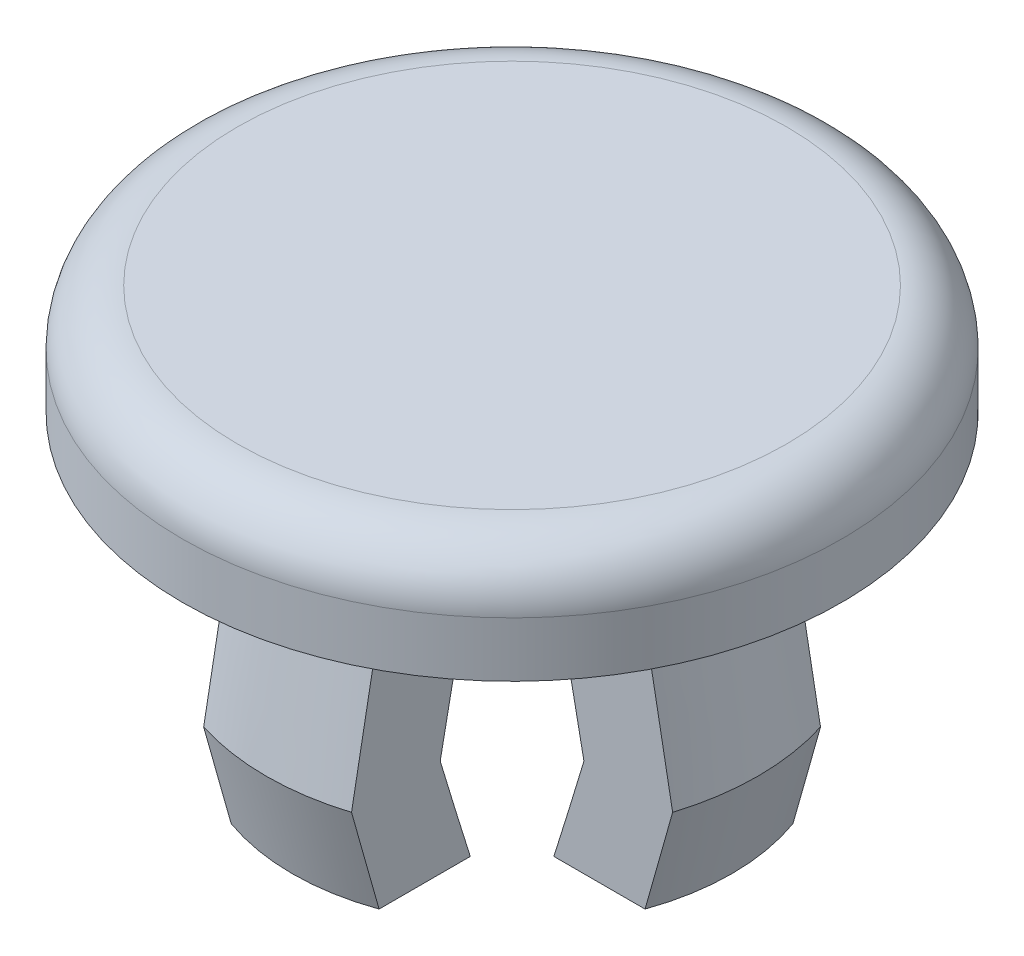
SolidWorks part; units mm, degrees
material "VeroWhite Plus"
ref_plane "Front Plane" through (0, 0, 0) normal (0, 0, 1) x (1, 0, 0)
ref_plane "Top Plane" through (0, 0, 0) normal (0, 1, 0) x (1, 0, 0)
ref_plane "Right Plane" through (0, 0, 0) normal (1, 0, 0) x (0, 0, -1)
sketch "Sketch0" plane through (0, 0, 0) normal (0, 0, 1) x (1, 0, 0)
  line L1 (0, -3.5) -> (0, 2) construction
  line L2 (-6, 2) -> (6, 2) construction
  line L3 (-4, -3.5) -> (4, -3.5) construction
  point P7 (0, -0.8)
  dimension "D" = 12
  dimension "B MAX" = 3.5
  dimension "A" = 8
  dimension "H" = 2
  dimension "B MIN" = 0.8
sketch "Sketch1" plane through (0, 0, 0) normal (0, 0, 1) x (1, 0, 0)
  line L0 (0, 2) -> (-5, 2)
  line L1 (-6, 1) -> (-6, 0)
  line L2 (-6, 1) -> (0, 1) construction
  line L4 (0, 2) -> (0, 0)
  line L5 (0, -3.5) -> (0, 2) construction
  line L7 (0, 0) -> (-6, 0)
  arc A0 (-5, 2) -> (-6, 1) centre (-5, 1) ccw
revolve "Revolve1" add sketch "Sketch1" angle 360 about L4
sketch "Sketch2" plane through (0, 0, 0) normal (0, 0, 1) x (1, 0, 0)
  line L1 (-4, -3.5) -> (-4, -5.2768) construction
  line L2 (-2.9761, -3.5) -> (-4.4761, -3.5) construction
  line L3 (0, 0) -> (-6, 0) construction
  line L4 (-4.4761, -3.5) -> (-4.4761, -1.75) construction
  line L5 (-4.4761, -3.5) -> (-3.8589, 0)
  line L6 (-2.3589, 0) -> (-2.9761, -3.5)
  line L7 (-2.9761, -3.5) -> (-2.5, -5.2768)
  line L8 (-4, -5.2768) -> (-4.4761, -3.5)
  line L9 (-2.5, -5.2768) -> (-4, -5.2768)
  line L10 (-3.8589, 0) -> (-2.3589, 0)
  line L11 (0, -3.5) -> (0, 2) construction
  line L12 (0, -3.5) -> (0, 2) construction
  line L13 (-4, -3.5) -> (-4, -0.8) construction
  line L14 (-4, -0.8) -> (0, -0.8) construction
  line L15 (-4.4761, -1.75) -> (-4.4761, 0) construction
  dimension "D1" = 1.5
  dimension "D2" = 15
  dimension "D3" = 25
revolve "Revolve2" add sketch "Sketch2" angle 360 mid plane about L12
sketch "Sketch3" plane through (0, 0, 0) normal (0, 1, 0) x (1, 0, 0)
  line L0 (-4.2689, 1.346) -> (-1.346, 1.346)
  line L1 (0, 0) -> (-4.2689, -1.346) construction
  line L2 (0, 0) -> (-4.2689, 1.346) construction
  line L3 (-4.2689, 1.346) -> (-4.2689, -1.346) construction
  line L4 (-1.346, 1.346) -> (-1.346, 4.2689)
  line L5 (1.346, 1.346) -> (4.2689, 1.346)
  line L6 (1.346, 1.346) -> (1.346, 4.2689)
  line L7 (-1.346, 1.346) -> (1.346, 1.346) construction
  line L8 (1.346, 1.346) -> (1.346, -1.346) construction
  line L9 (1.346, -1.346) -> (-1.346, -1.346) construction
  line L10 (-1.346, -1.346) -> (-1.346, 1.346) construction
  line L11 (-1.346, -1.346) -> (-4.2689, -1.346)
  line L12 (-1.346, -1.346) -> (-1.346, -4.2689)
  line L13 (1.346, -1.346) -> (1.346, -4.2689)
  line L14 (1.346, -1.346) -> (4.2689, -1.346)
  arc A1 (-4.2689, -1.346) -> (-1.346, -4.2689) centre (0, 0) ccw
  arc A2 (-1.346, 4.2689) -> (-4.2689, 1.346) centre (0, 0) ccw
  arc A3 (4.2689, 1.346) -> (1.346, 4.2689) centre (0, 0) ccw
  arc A4 (1.346, -4.2689) -> (4.2689, -1.346) centre (0, 0) ccw
  circle A5 centre (0, 0) radius 4.4761 construction
  dimension "D1" = 35
extrude "Cut-Extrude1" cut sketch "Sketch3" against normal through all
